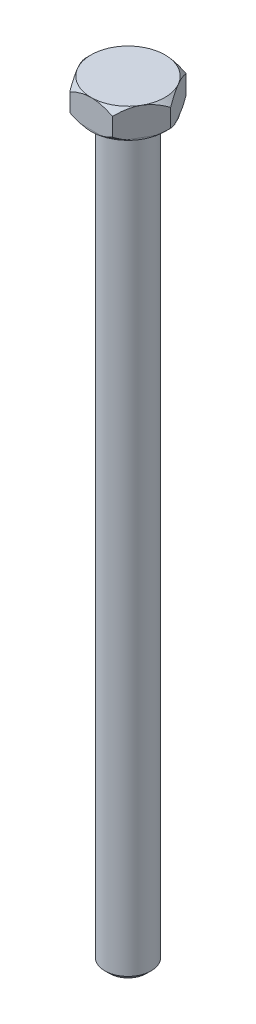
SolidWorks part; units mm, degrees
material "Cast Stainless Steel"
ref_plane "Front Plane" through (0, 0, 0) normal (0, 0, 1) x (1, 0, 0)
ref_plane "Top Plane" through (0, 0, 0) normal (0, 1, 0) x (1, 0, 0)
ref_plane "Right Plane" through (0, 0, 0) normal (1, 0, 0) x (0, 0, -1)
sketch "Sketch1" plane through (0, 0, 0) normal (0, 1, 0) x (1, 0, 0)
  line L0 (0, 0) -> (9.2376, 0) construction
  line L1 (9.2376, 0) -> (4.6188, 8)
  line L2 (4.6188, 8) -> (-4.6188, 8)
  line L3 (-4.6188, 8) -> (-9.2376, 0)
  line L4 (-9.2376, 0) -> (-4.6188, -8)
  line L5 (-4.6188, -8) -> (4.6188, -8)
  line L6 (4.6188, -8) -> (9.2376, 0)
  circle A0 centre (0, 0) radius 8 construction
  dimension "D1" = 16
extrude "Boss-Extrude1" add sketch "Sketch1" against normal blind 6.4
sketch "Sketch4" plane through (0, 0, 0) normal (1, 0, 0) x (0, 0, -1)
  line L0 (-8, 0) -> (-9.2376, 0)
  line L1 (-9.2376, 0) -> (-9.2376, -1.2376)
  line L2 (-9.2376, -1.2376) -> (-8, 0)
  line L3 (-8, -3.2) -> (8, -3.2) construction
  line L4 (-9.2376, -5.1624) -> (-8, -6.4)
  line L5 (-9.2376, -6.4) -> (-9.2376, -5.1624)
  line L6 (-8, -6.4) -> (-9.2376, -6.4)
  line L7 (0, 0) -> (0, -3.2) construction
  dimension "D1" = 45
  dimension "D2" = 3.2
  dimension "D4" = 16
  dimension "D3" = 9.2376
revolve "Cut-Revolve1" cut sketch "Sketch4" angle 360 about L7
sketch "Sketch2" plane through (0, -6.4, 0) normal (0, -1, 0) x (1, 0, 0)
  circle A0 centre (0, 0) radius 8
  dimension "D1" = 16
extrude "Cut-Extrude1" cut sketch "Sketch2" against normal blind 0.32 flip side to cut
sketch "Sketch3" plane through (0, -6.4, 0) normal (0, -1, 0) x (1, 0, 0)
  circle A0 centre (0, 0) radius 5
  dimension "D1" = 10
extrude "Boss-Extrude2" add sketch "Sketch3" along normal blind 160
chamfer "Chamfer1" distance 1 angle 45 1 edges at (0, -166.4, -5)
equation "\"k\"= 6.4"
equation "\"e\"= 17.77"
equation "\"S\"= 16"
equation "\"L\"= 160"
equation "\"D1@Sketch1\"=\"S\""
equation "\"D1@Boss-Extrude1\"=\"k\""
equation "\"D1@Sketch2\"=\"S\""
equation "\"D1@Cut-Extrude1\"=\"k\"/20"
equation "\"d\"= 10"
equation "\"D1@Sketch3\"=\"d\""
equation "\"D1@Boss-Extrude2\"=\"L\""
equation "\"D2@Sketch4\"=\"k\"/2"
equation "\"D3@Sketch4\"= \"S\" / sqr(3)"
equation "\"D4@Sketch4\"= \"S\""
equation "\"D1@Chamfer1\"=\"d\"/10"
